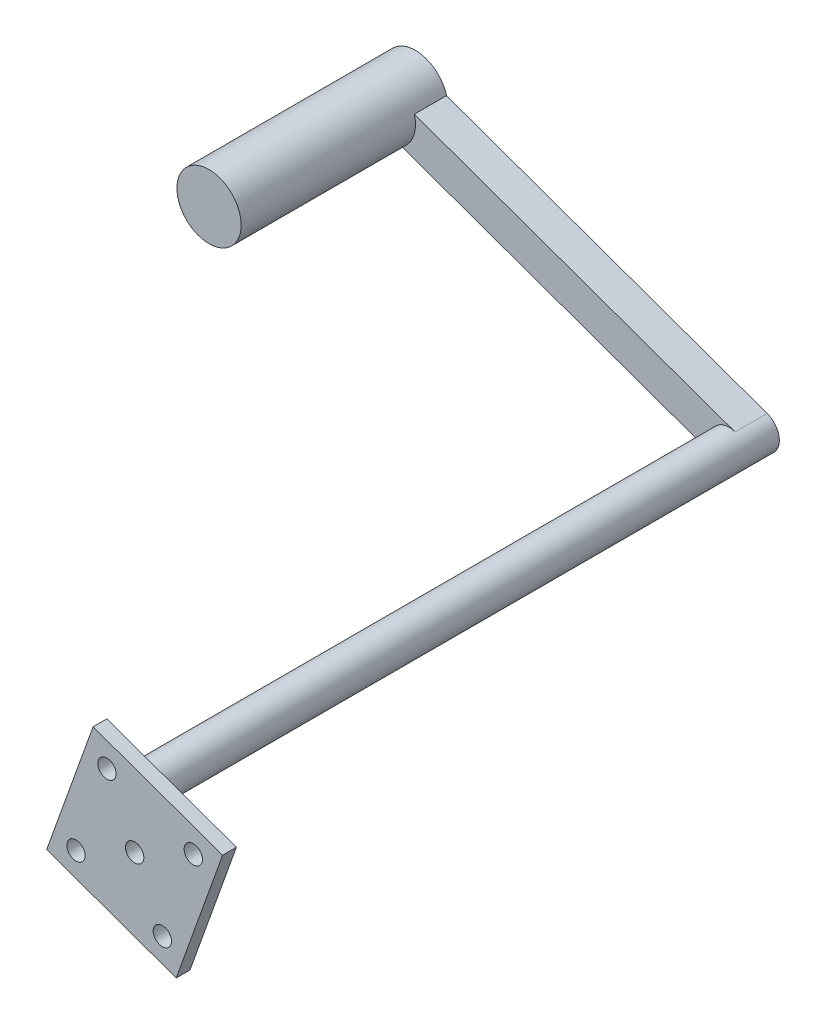
SolidWorks part; units mm, degrees
ref_plane "前视基准面" through (0, 0, 0) normal (0, 0, 1) x (1, 0, 0)
ref_plane "上视基准面" through (0, 0, 0) normal (0, 1, 0) x (1, 0, 0)
ref_plane "右视基准面" through (0, 0, 0) normal (1, 0, 0) x (0, 0, -1)
other "Configuration Table"
sketch "草图1" plane through (0, 0, 0) normal (0, 0, 1) x (1, 0, 0)
  circle A0 centre (-86.6066, -63.7835) radius 7
extrude "凸台-拉伸1" add sketch "草图1" along normal blind 45
sketch "草图3" plane through (0, 0, 0) normal (0, 0, -1) x (-1, 0, 0)
  line L0 (86.6066, -63.7835) -> (11.2929, -90.7622) construction
  line L1 (87.9556, -67.5492) -> (12.6419, -94.5278)
  line L2 (85.2577, -60.0178) -> (9.944, -86.9965)
  arc A0 (87.9556, -67.5492) -> (85.2577, -60.0178) centre (86.6066, -63.7835) ccw
  arc A1 (9.944, -86.9965) -> (12.6419, -94.5278) centre (11.2929, -90.7622) ccw
  point P2 (48.9498, -77.2728)
extrude "凸台-拉伸2" add sketch "草图3" against normal blind 7
sketch "草图7" plane through (0, 0, 7) normal (0, 0, 1) x (1, 0, 0)
  circle A3 centre (-11.2929, -90.7622) radius 4
extrude "凸台-拉伸3" add sketch "草图7" along normal blind 135
sketch "草图8" plane through (0, 0, 142) normal (0, 0, 1) x (1, 0, 0)
  line L0 (-12.6419, -94.5278) -> (-82.5475, -69.4865) construction
  line L3 (-11.2929, -90.7622) -> (22.1323, -102.7356) construction
  line L4 (-11.883, -74.6174) -> (16.3597, -84.7344)
  line L5 (16.3597, -84.7344) -> (6.2427, -112.9771)
  line L6 (-9.944, -86.9965) -> (-12.6419, -94.5278) construction
  line L7 (6.2427, -112.9771) -> (-22, -102.8601)
  line L8 (-22, -102.8601) -> (-11.883, -74.6174)
  circle A0 centre (-8.862, -81.0107) radius 2
  circle A1 centre (9.9664, -87.7554) radius 2
  circle A3 centre (-15.6067, -99.8391) radius 2
  circle A4 centre (3.2217, -106.5838) radius 2
  circle A5 centre (-2.8202, -93.7973) radius 2
  point P9 (-11.2929, -90.7622)
  point P13 (-0.7806, -94.5278)
  dimension "D1" = 30
  dimension "D2" = 30
  dimension "D5" = 5
  dimension "D10" = 5
  dimension "D11" = 15
  dimension "D3" = 5
  dimension "D4" = 5
  dimension "D6" = 5
  dimension "D7" = 5
  dimension "D8" = 5
  dimension "D9" = 5
  dimension "D12" = 15
  dimension "D13" = 9
extrude "凸台-拉伸4" add sketch "草图8" along normal blind 3
